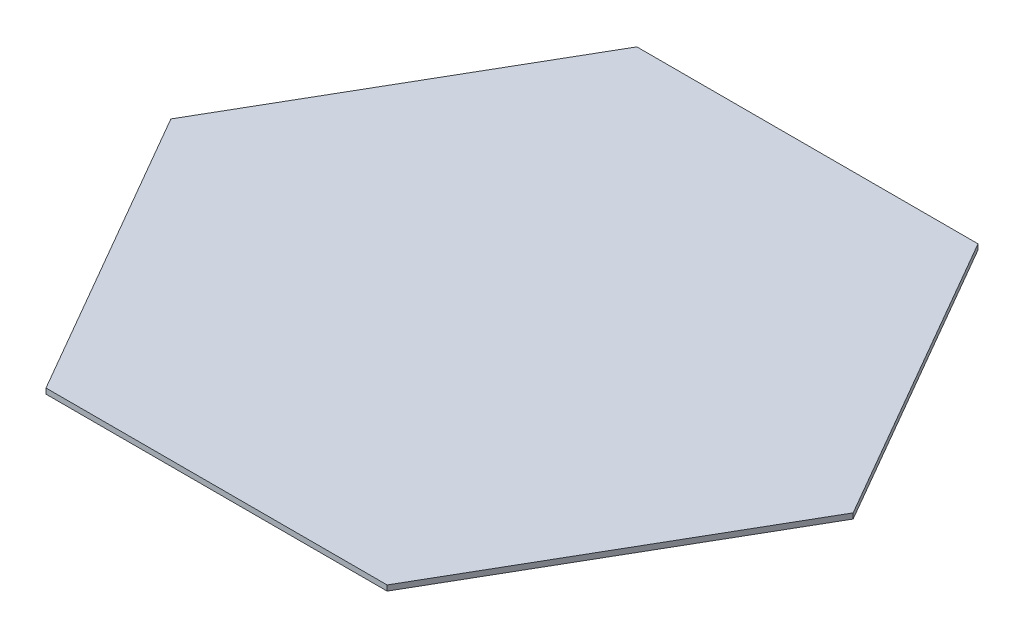
SolidWorks part; units mm, degrees
ref_plane "Front Plane" through (0, 0, 0) normal (0, 0, 1) x (1, 0, 0)
ref_plane "Top Plane" through (0, 0, 0) normal (0, 1, 0) x (1, 0, 0)
ref_plane "Right Plane" through (0, 0, 0) normal (1, 0, 0) x (0, 0, -1)
sketch "Sketch1" plane through (0, 0, 0) normal (0, 1, 0) x (1, 0, 0)
  line L1 (-63.5, 0) -> (-31.75, -54.9926)
  line L2 (-31.75, -54.9926) -> (31.75, -54.9926)
  line L3 (31.75, -54.9926) -> (63.5, 0)
  line L4 (63.5, 0) -> (31.75, 54.9926)
  line L5 (31.75, 54.9926) -> (-31.75, 54.9926)
  line L6 (-31.75, 54.9926) -> (-63.5, 0)
  circle A0 centre (0, 0) radius 54.9926 construction
  dimension "D1" = 63.5
extrude "Boss-Extrude1" add sketch "Sketch1" along normal blind 1
